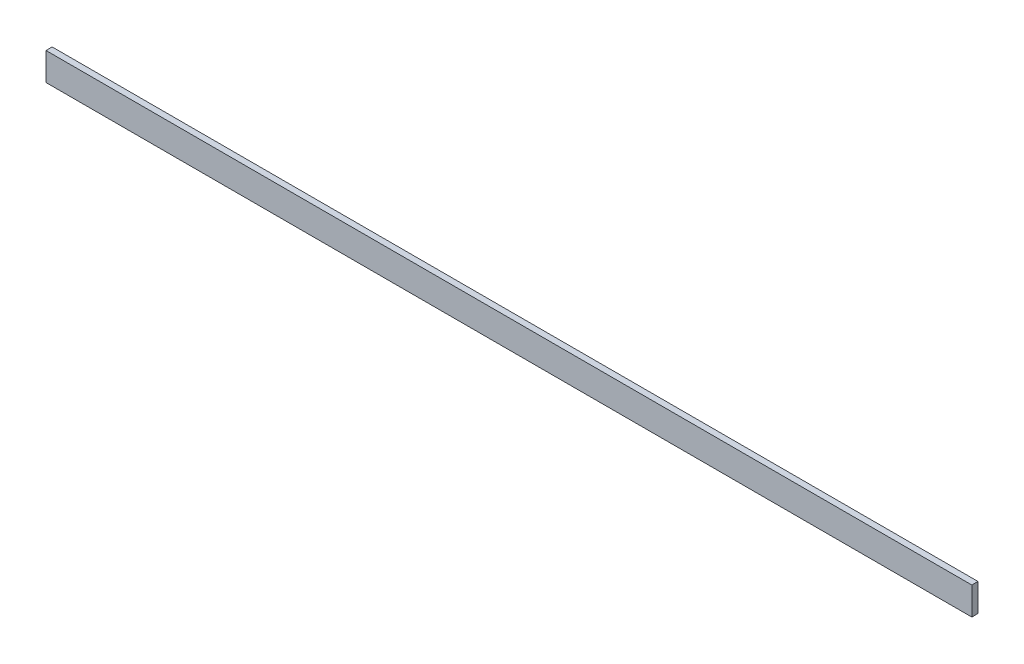
SolidWorks part; units mm, degrees
ref_plane "Plan de face" through (0, 0, 0) normal (0, 0, 1) x (1, 0, 0)
ref_plane "Plan de dessus" through (0, 0, 0) normal (0, 1, 0) x (1, 0, 0)
ref_plane "Plan de droite" through (0, 0, 0) normal (1, 0, 0) x (0, 0, -1)
sketch "Esquisse1" plane through (0, 0, 0) normal (0, 0, 1) x (1, 0, 0)
  line L1 (-123.6211, 34.7998) -> (2876.3789, 34.7998)
  line L2 (-123.6211, 34.7998) -> (-123.6211, -55.2002)
  line L3 (-123.6211, -55.2002) -> (2876.3789, -55.2002)
  line L4 (2876.3789, 34.7998) -> (2876.3789, -55.2002)
  dimension "D1" = 3000
  dimension "D2" = 90
extrude "Boss.-Extru.1" add sketch "Esquisse1" along normal blind 20
